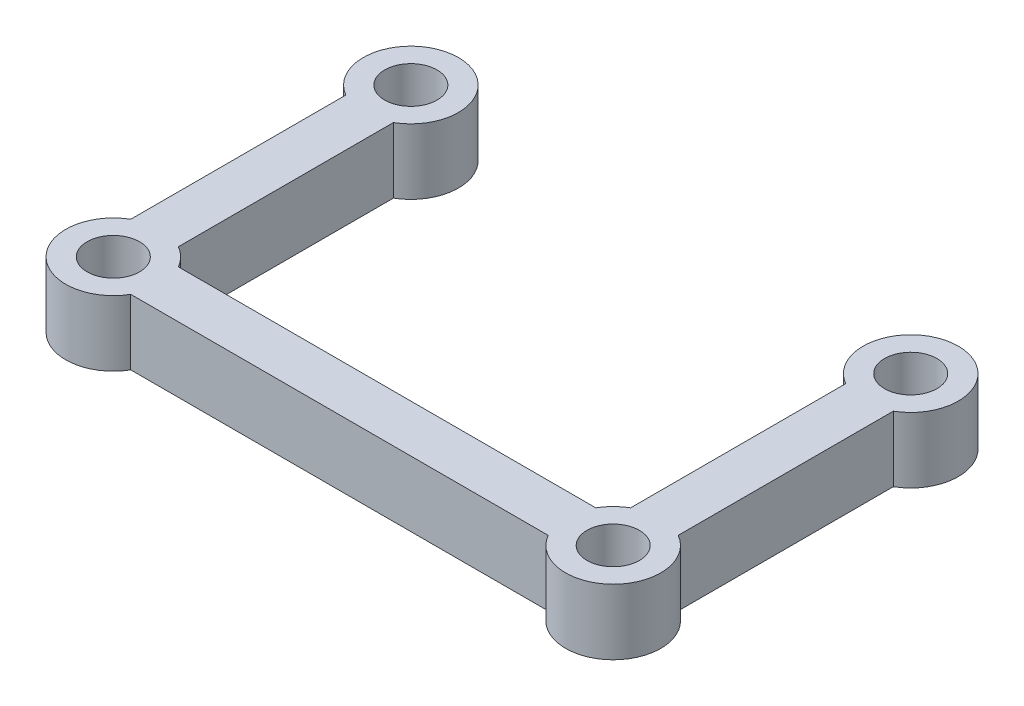
SolidWorks part; units mm, degrees
ref_plane "Front Plane" through (0, 0, 0) normal (0, 0, 1) x (1, 0, 0)
ref_plane "Top Plane" through (0, 0, 0) normal (0, 1, 0) x (1, 0, 0)
ref_plane "Right Plane" through (0, 0, 0) normal (1, 0, 0) x (0, 0, -1)
sketch "Main" plane through (0, 0, 0) normal (0, 1, 0) x (1, 0, 0)
  line L0 (-21, 12.5) -> (-21, 0) construction
  line L1 (-21, 0) -> (0, 0) construction
  line L2 (0, 0) -> (0, 12.5) construction
  line L3 (-19.2679, 1) -> (-1.7321, 1)
  line L4 (-19.2679, -1) -> (-1.7321, -1)
  line L5 (-22, 10.7679) -> (-22, 1.7321)
  line L6 (-20, 10.7679) -> (-20, 1.7321)
  line L7 (-1, 10.7679) -> (-1, 1.7321)
  line L8 (1, 10.7679) -> (1, 1.7321)
  arc A0 (-1, 1.7321) -> (-1.7321, 1) centre (0, 0) ccw
  arc A1 (-22, 1.7321) -> (-19.2679, -1) centre (-21, 0) ccw
  arc A2 (-20, 10.7679) -> (-22, 10.7679) centre (-21, 12.5) ccw
  arc A3 (1, 10.7679) -> (-1, 10.7679) centre (0, 12.5) ccw
  arc A6 (-1.7321, -1) -> (1, 1.7321) centre (0, 0) ccw
  arc A7 (-19.2679, 1) -> (-20, 1.7321) centre (-21, 0) ccw
  dimension "D2" = 4
  dimension "D10" = 2
  dimension "D11" = 2
  dimension "D1" = 12.5
  dimension "D3" = 21
  dimension "D4" = 1
  dimension "D5" = 1
  dimension "D6" = 1
  dimension "D7" = 1
  dimension "D8" = 1
  dimension "D9" = 1
extrude "ExtudeMain" add sketch "Main" along normal blind 2.75
sketch "Sketch2" plane through (0, 2.75, 0) normal (0, 1, 0) x (1, 0, 0)
  circle A0 centre (-21, 12.5) radius 1.1
  circle A1 centre (0, 12.5) radius 1.1
  circle A2 centre (0, 0) radius 1.1
  circle A3 centre (-21, 0) radius 1.1
  dimension "D1" = 2.2
extrude "PiHoles" cut sketch "Sketch2" against normal up to next
equation "\"Thick\"= 1mm"
equation "\"D4@Main\" = \"Thick\""
equation "\"D5@Main\" = \"Thick\""
equation "\"D7@Main\" = \"Thick\""
equation "\"D8@Main\" = \"Thick\""
equation "\"D9@Main\" = \"Thick\""
equation "\"CircSize\"= 4mm"
equation "\"D2@Main\" = \"CircSize\""
equation "\"D10@Main\" = \"CircSize\" / 2"
equation "\"D11@Main\" = \"CircSize\" / 2"
equation "\"D6@Main\"=\"Thick\""
